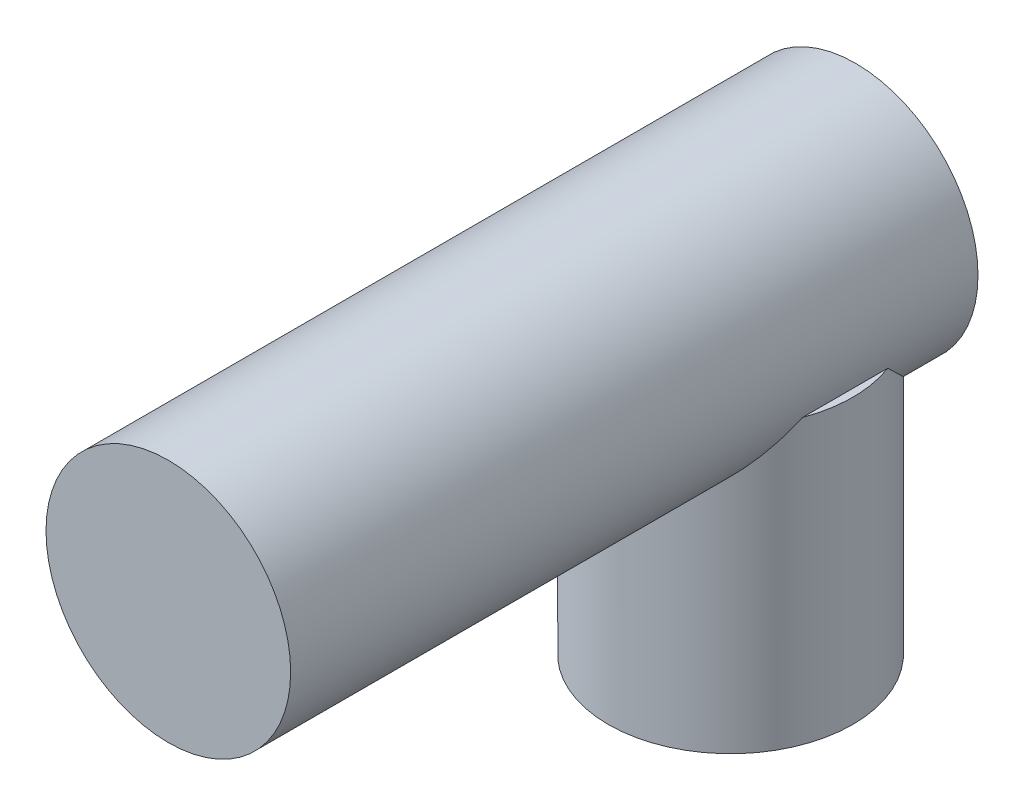
SolidWorks part; units mm, degrees
material "ABS"
ref_plane "Front Plane" through (0, 0, 0) normal (0, 0, 1) x (1, 0, 0)
ref_plane "Top Plane" through (0, 0, 0) normal (0, 1, 0) x (1, 0, 0)
ref_plane "Right Plane" through (0, 0, 0) normal (1, 0, 0) x (0, 0, -1)
sketch "Sketch2" plane through (0, 0, 0) normal (0, 0, 1) x (1, 0, 0)
  circle A0 centre (-32.9798, 24.7348) radius 26.25
  dimension "D1" = 52.5
extrude "Boss-Extrude2" add sketch "Sketch2" along normal blind 147.5
sketch "Sketch3" plane through (0, 0, 0) normal (0, 1, 0) x (1, 0, 0)
  circle A0 centre (-33.0435, -26.794) radius 26.25
  point P2 (0, 0)
  dimension "D1" = 52.5
extrude "Boss-Extrude4" add sketch "Sketch3" along normal blind 15.416 and the other way blind 45.4
equation "\"4.5cmin\"=4.54"
